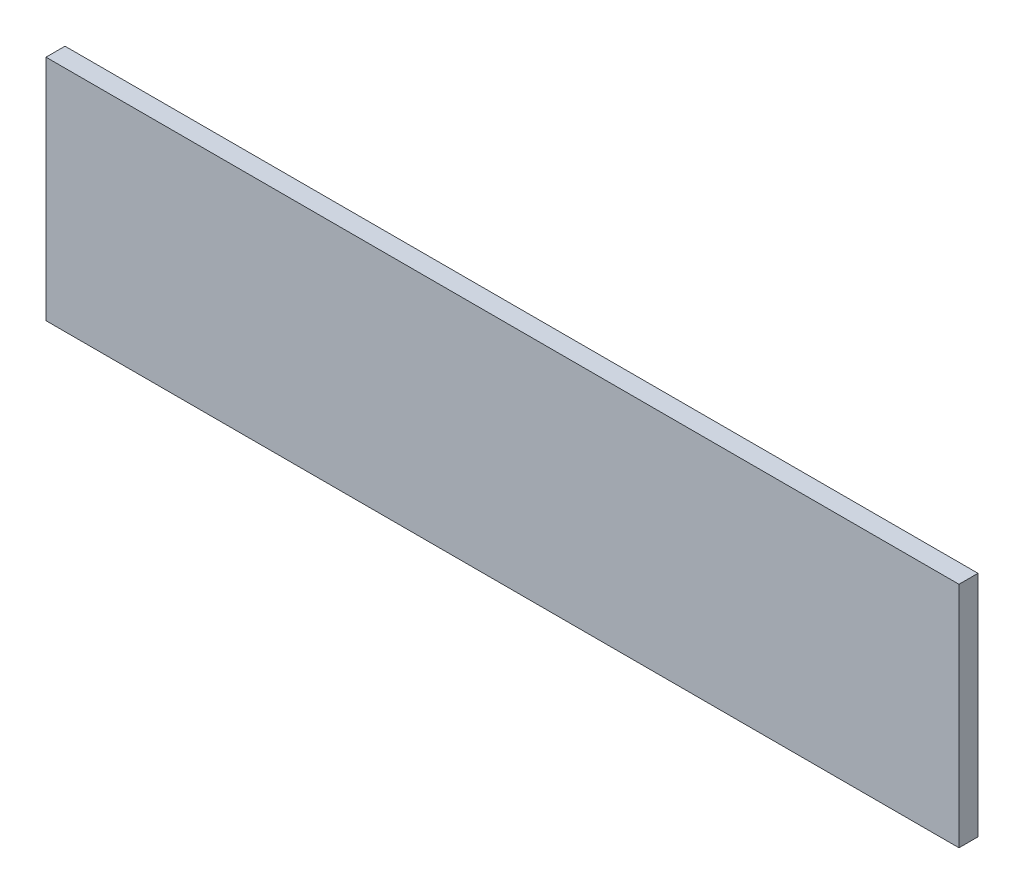
SolidWorks part; units mm, degrees
ref_plane "Front Plane" through (0, 0, 0) normal (0, 0, 1) x (1, 0, 0)
ref_plane "Top Plane" through (0, 0, 0) normal (0, 1, 0) x (1, 0, 0)
ref_plane "Right Plane" through (0, 0, 0) normal (1, 0, 0) x (0, 0, -1)
sketch "Sketch1" plane through (0, 0, 0) normal (0, 0, 1) x (1, 0, 0)
  line L1 (1219.2, -304.8) -> (-1219.2, -304.8)
  line L2 (1219.2, -304.8) -> (1219.2, 304.8)
  line L3 (1219.2, 304.8) -> (-1219.2, 304.8)
  line L4 (-1219.2, -304.8) -> (-1219.2, 304.8)
  line L5 (1219.2, -304.8) -> (-1219.2, 304.8) construction
  line L6 (1219.2, 304.8) -> (-1219.2, -304.8) construction
  point P0 (0, 0)
  point P7 (-1219.2, 304.8)
  point P8 (1219.2, 304.8)
  point P9 (1219.2, -304.8)
  point P10 (-1219.2, -304.8)
  dimension "Length" = 2438.4
  dimension "Width" = 609.6
sketch "Sketch2" plane through (0, 0, 0) normal (1, 0, 0) x (0, 0, -1)
  line L1 (25.4, -304.8) -> (-25.4, -304.8)
  line L2 (25.4, -304.8) -> (25.4, 304.8)
  line L3 (25.4, 304.8) -> (-25.4, 304.8)
  line L4 (-25.4, -304.8) -> (-25.4, 304.8)
  line L5 (25.4, -304.8) -> (-25.4, 304.8) construction
  line L6 (25.4, 304.8) -> (-25.4, -304.8) construction
  point P0 (0, 0)
  dimension "Thickness" = 50.8
sketch "Sketch3" plane through (0, 0, 0) normal (0, 0, 1) x (1, 0, 0)
  line L0 (-1219.2, -304.8) -> (-1219.2, 304.8) construction
  line L1 (1219.2, -304.8) -> (-1219.2, -304.8) construction
  line L2 (1219.2, -304.8) -> (1219.2, 304.8) construction
  line L3 (1219.2, 304.8) -> (-1219.2, 304.8) construction
  line L4 (-1219.2, -304.8) -> (-1219.2, 304.8)
  line L5 (1219.2, -304.8) -> (-1219.2, -304.8)
  line L6 (1219.2, -304.8) -> (1219.2, 304.8)
  line L7 (1219.2, 304.8) -> (-1219.2, 304.8)
extrude "Boss-Extrude1" add sketch "Sketch3" against normal up to vertex (25.4 mm away) and the other way up to vertex (25.4 mm away) up to point (0, 304.8, -25.4) other way up to point (0, 304.8, 25.4)
